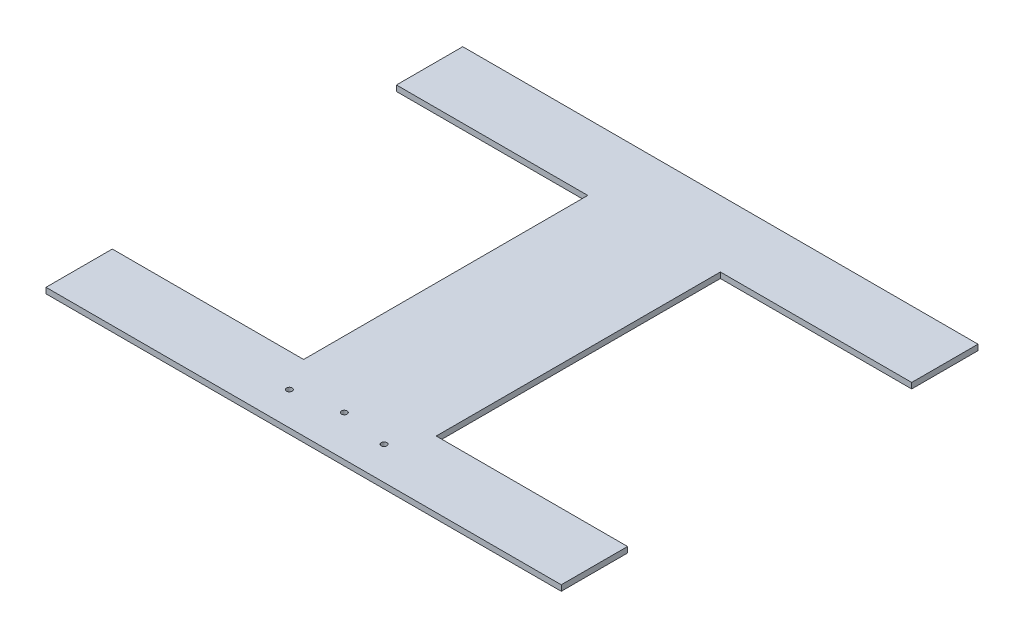
SolidWorks part; units mm, degrees
material "Acrylic (Medium-high impact)"
ref_plane "Front Plane" through (0, 0, 0) normal (0, 0, 1) x (1, 0, 0)
ref_plane "Top Plane" through (0, 0, 0) normal (0, 1, 0) x (1, 0, 0)
ref_plane "Right Plane" through (0, 0, 0) normal (1, 0, 0) x (0, 0, -1)
sketch "Sketch1" plane through (0, 0, 0) normal (0, 1, 0) x (1, 0, 0)
  line L1 (136, 110) -> (-136, 110)
  line L2 (136, 110) -> (136, -110)
  line L3 (136, -110) -> (-136, -110)
  line L4 (-136, 110) -> (-136, -110)
  line L5 (136, 110) -> (-136, -110) construction
  line L6 (136, -110) -> (-136, 110) construction
  point P0 (0, 0)
  dimension "D1" = 272
  dimension "D2" = 220
extrude "Boss-Extrude1" add sketch "Sketch1" along normal blind 3
sketch "Sketch2" plane through (0, 3, 0) normal (0, 1, 0) x (1, 0, 0)
  line L0 (-136, 110) -> (136, -110) construction
  line L1 (-136, -110) -> (136, 110) construction
  line L2 (136, 110) -> (136, 0) construction
  line L3 (136, -110) -> (136, 110) construction
  line L4 (136, 0) -> (-136, 0) construction
  line L5 (-136, 110) -> (-136, -110) construction
  line L6 (-136, 0) -> (0, 110) construction
  line L7 (136, 110) -> (-136, 110) construction
  line L8 (0, 110) -> (0, -110) construction
  line L9 (-136, -110) -> (136, -110) construction
  line L10 (-136, 110) -> (136, 110)
  line L15 (-136, 110) -> (-136, 75)
  line L16 (-136, 75) -> (-35, 75)
  line L21 (-35, 75) -> (-35, -75)
  line L26 (136, 110) -> (136, 75)
  line L27 (136, 75) -> (35, 75)
  line L28 (35, 75) -> (35, -75)
  line L29 (-136, -110) -> (136, -110)
  line L30 (136, -110) -> (136, -75)
  line L31 (136, -75) -> (35, -75)
  line L32 (-136, -110) -> (-136, -75)
  line L33 (-136, -75) -> (-35, -75)
  point P28 (35, 0)
  point P30 (-35, 0)
  dimension "D1" = 35
  dimension "D2" = 35
extrude "Cut-Extrude1" cut sketch "Sketch2" against normal through all flip side to cut
sketch "Sketch3" plane through (0, 0, 0) normal (0, -1, 0) x (1, 0, 0)
  circle A0 centre (25, 92.5) radius 1.5
  circle A1 centre (-25, 92.5) radius 1.5
  dimension "D1" = 3
  dimension "D2" = 3
extrude "Cut-Extrude2" cut sketch "Sketch3" against normal through all
sketch "Sketch5" plane through (0, 0, 0) normal (0, -1, 0) x (1, 0, 0)
  circle A0 centre (0, 88.5) radius 1.5
  dimension "D1" = 3
extrude "Cut-Extrude4" cut sketch "Sketch5" against normal through all
